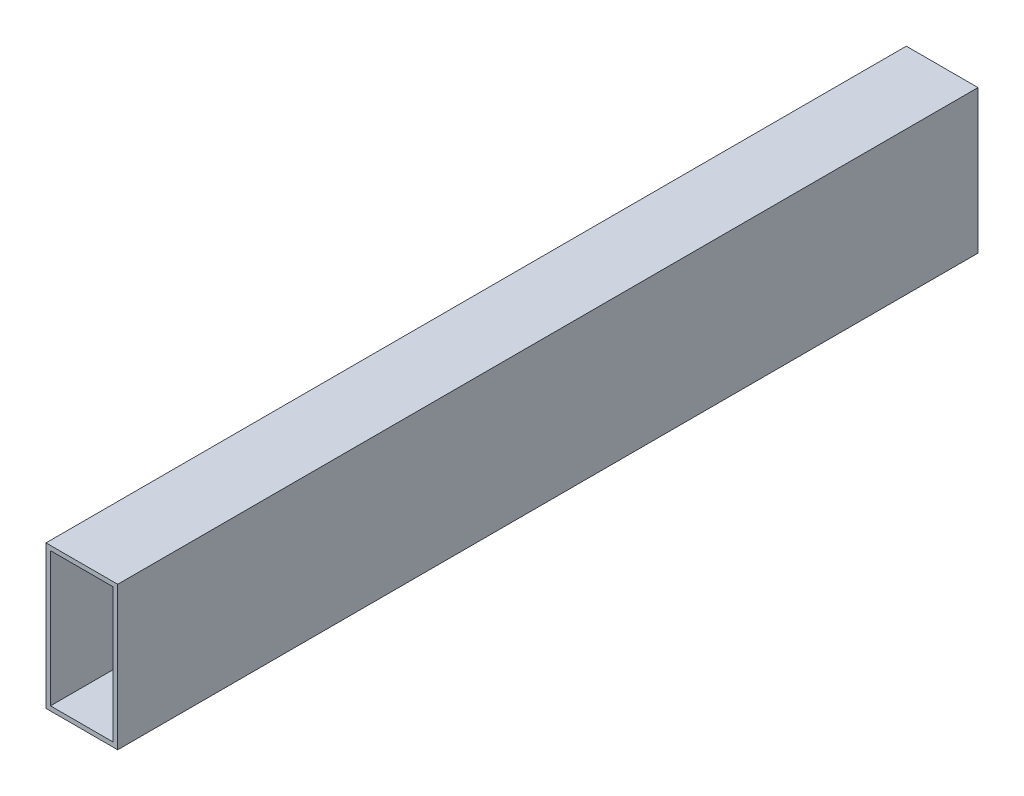
SolidWorks part; units mm, degrees
ref_plane "Front Plane" through (0, 0, 0) normal (0, 0, 1) x (1, 0, 0)
ref_plane "Top Plane" through (0, 0, 0) normal (0, 1, 0) x (1, 0, 0)
ref_plane "Right Plane" through (0, 0, 0) normal (1, 0, 0) x (0, 0, -1)
sketch "Sketch1" plane through (0, 0, 0) normal (0, 0, 1) x (1, 0, 0)
  line L1 (0, 0) -> (25.4, 0)
  line L2 (0, 0) -> (0, 50.8)
  line L3 (0, 50.8) -> (25.4, 50.8)
  line L4 (25.4, 0) -> (25.4, 50.8)
  dimension "D1" = 25.4
  dimension "D2" = 50.8
extrude "Extrude-Thin1" add sketch "Sketch1" along normal blind 304.8 thin thin type one direction reverse wall 1.5875
